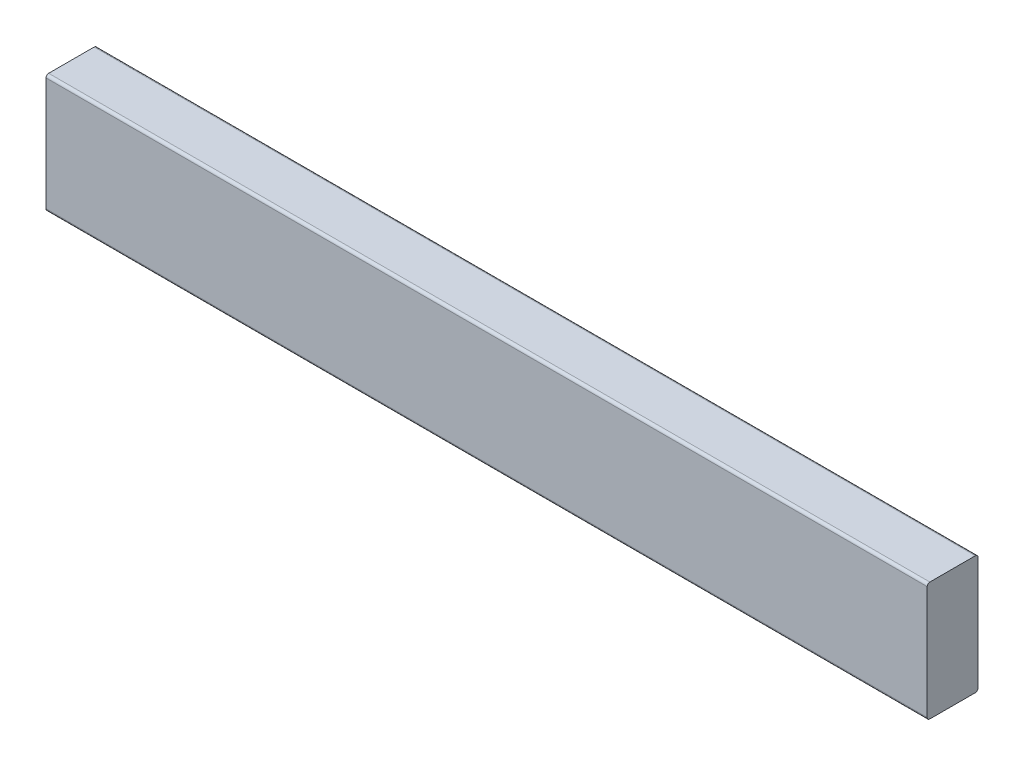
SolidWorks part; units mm, degrees
ref_plane "Front Plane" through (0, 0, 0) normal (0, 0, 1) x (1, 0, 0)
ref_plane "Top Plane" through (0, 0, 0) normal (0, 1, 0) x (1, 0, 0)
ref_plane "Right Plane" through (0, 0, 0) normal (1, 0, 0) x (0, 0, -1)
sketch "Sketch1" plane through (0, 0, 0) normal (1, 0, 0) x (0, -1, 0)
  line L1 (-44.45, -19.05) -> (44.45, -19.05)
  line L2 (-44.45, -19.05) -> (-44.45, 19.05)
  line L3 (-44.45, 19.05) -> (44.45, 19.05)
  line L4 (44.45, -19.05) -> (44.45, 19.05)
  line L5 (-44.45, -19.05) -> (44.45, 19.05) construction
  line L6 (-44.45, 19.05) -> (44.45, -19.05) construction
  point P0 (0, 0)
  dimension "D1" = 38.1
  dimension "D2" = 88.9
extrude "Boss-Extrude1" add sketch "Sketch1" along normal blind 660.4
fillet "Fillet1" radius 2 4 edges at (330.2, 44.45, -19.05) (330.2, -44.45, -19.05) (330.2, -44.45, 19.05) (330.2, 44.45, 19.05)
